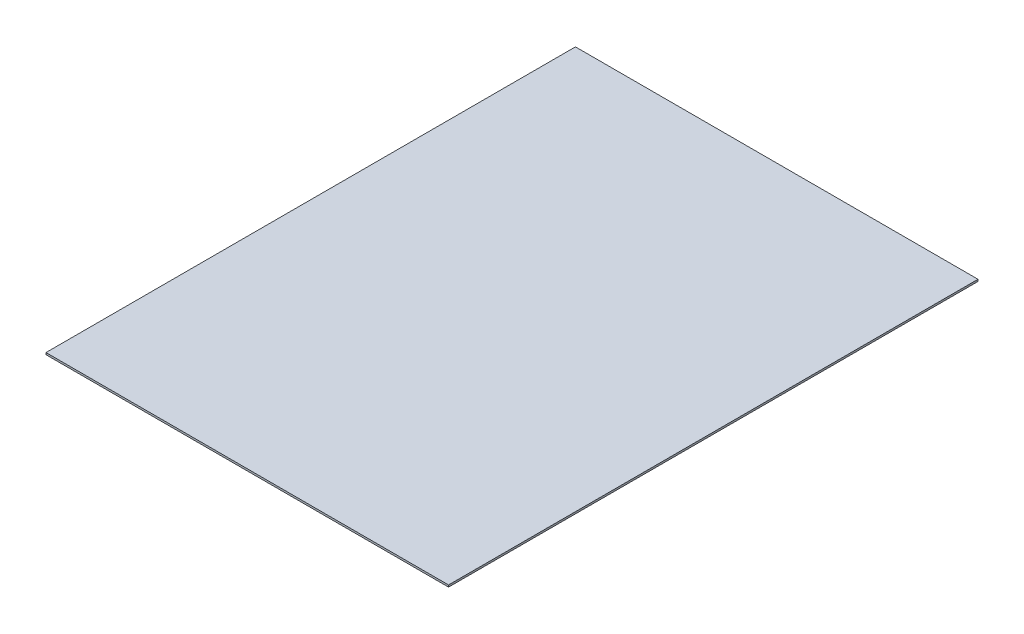
SolidWorks part; units mm, degrees
ref_plane "Front Plane" through (0, 0, 0) normal (0, 0, 1) x (1, 0, 0)
ref_plane "Top Plane" through (0, 0, 0) normal (0, 1, 0) x (1, 0, 0)
ref_plane "Right Plane" through (0, 0, 0) normal (1, 0, 0) x (0, 0, -1)
sketch "Sketch1" plane through (0, 0, 0) normal (0, 1, 0) x (1, 0, 0)
  line L1 (-737.5, -970) -> (737.5, -970)
  line L2 (-737.5, -970) -> (-737.5, 970)
  line L3 (-737.5, 970) -> (737.5, 970)
  line L4 (737.5, -970) -> (737.5, 970)
  line L5 (-737.5, -970) -> (737.5, 970) construction
  line L6 (-737.5, 970) -> (737.5, -970) construction
  point P0 (0, 0)
  dimension "D1" = 1475
  dimension "D2" = 1940
extrude "Boss-Extrude1" add sketch "Sketch1" along normal blind 7
